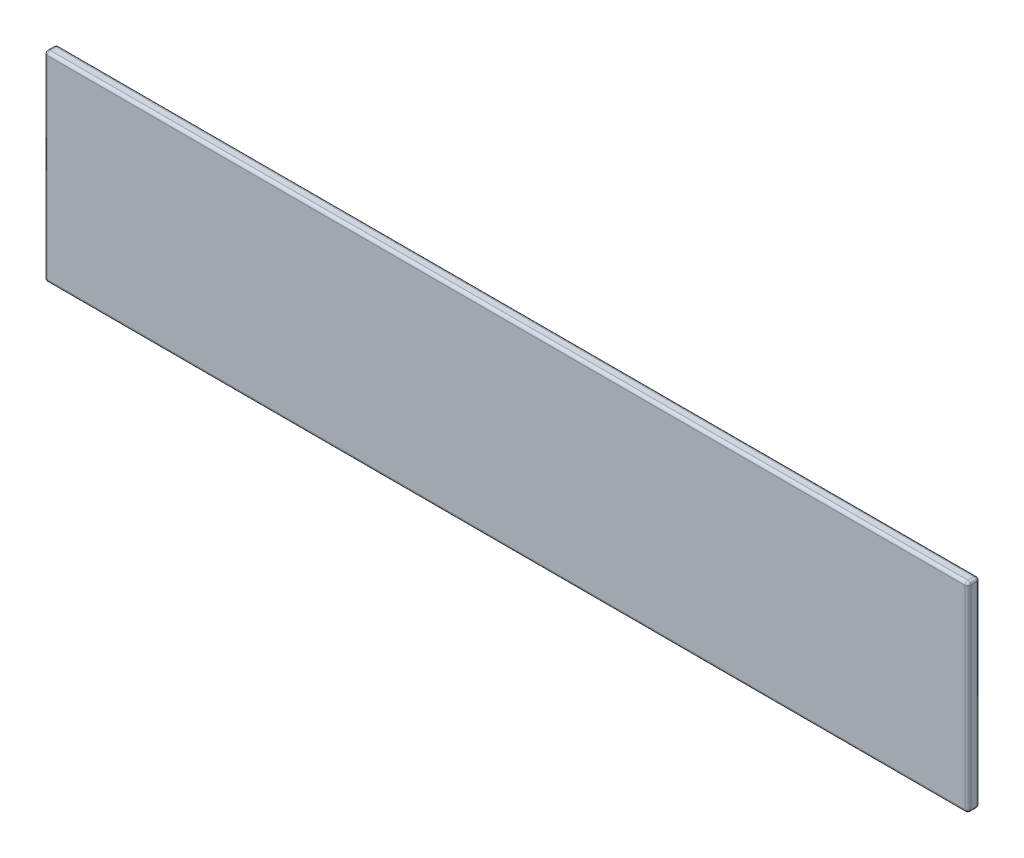
SolidWorks part; units mm, degrees
ref_plane "Front Plane" through (0, 0, 0) normal (0, 0, 1) x (1, 0, 0)
ref_plane "Top Plane" through (0, 0, 0) normal (0, 1, 0) x (1, 0, 0)
ref_plane "Right Plane" through (0, 0, 0) normal (1, 0, 0) x (0, 0, -1)
sketch "Sketch1" plane through (0, 0, 0) normal (0, 0, 1) x (1, 0, 0)
  line L1 (-77.35, -16.75) -> (77.35, -16.75)
  line L2 (-77.35, -16.75) -> (-77.35, 16.75)
  line L3 (-77.35, 16.75) -> (77.35, 16.75)
  line L4 (77.35, -16.75) -> (77.35, 16.75)
  line L5 (-77.35, -16.75) -> (77.35, 16.75) construction
  line L6 (-77.35, 16.75) -> (77.35, -16.75) construction
  point P0 (0, 0)
  dimension "D1" = 154.7
  dimension "D2" = 33.5
extrude "Boss-Extrude1" add sketch "Sketch1" along normal blind 2
fillet "Fillet1" radius 0.5 12 edges at (0, -16.75, 2) (0, -16.75, 0) (-77.35, 0, 2) (-77.35, -16.75, 1) (-77.35, 0, 0) (0, 16.75, 2) (-77.35, 16.75, 1) (0, 16.75, 0) (77.35, -16.75, 1) (77.35, 0, 2) (77.35, 16.75, 1) (77.35, 0, 0)
